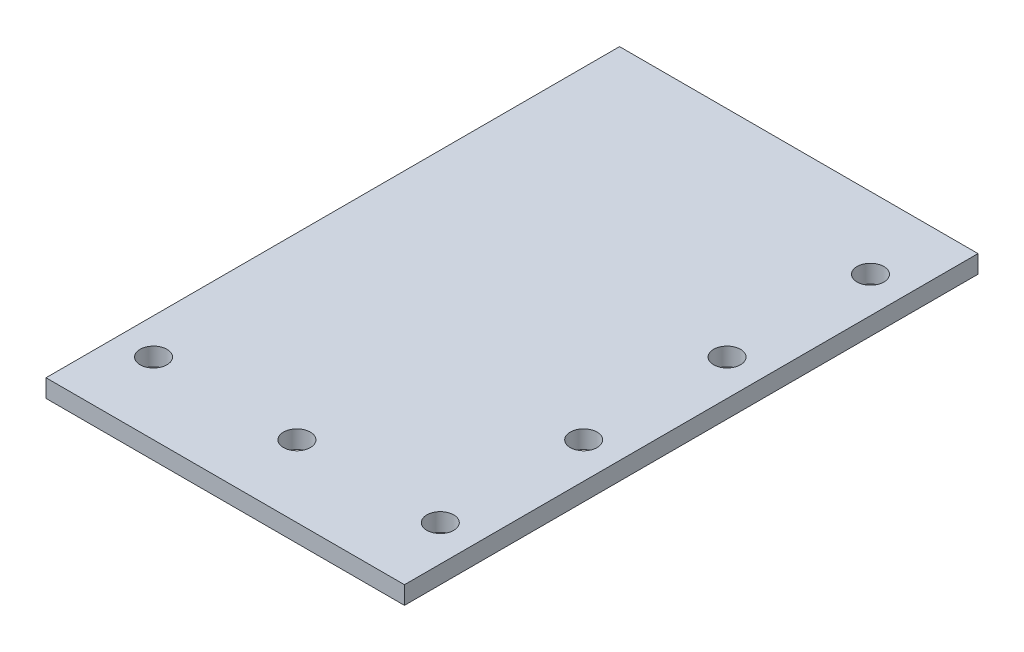
SolidWorks part; units mm, degrees
ref_plane "Front Plane" through (0, 0, 0) normal (0, 0, 1) x (1, 0, 0)
ref_plane "Top Plane" through (0, 0, 0) normal (0, 1, 0) x (1, 0, 0)
ref_plane "Right Plane" through (0, 0, 0) normal (1, 0, 0) x (0, 0, -1)
sketch "Sketch1" plane through (0, 0, 0) normal (0, 1, 0) x (1, 0, 0)
  line L1 (-31.75, 50.8) -> (31.75, 50.8)
  line L2 (-31.75, 50.8) -> (-31.75, -50.8)
  line L3 (-31.75, -50.8) -> (31.75, -50.8)
  line L4 (31.75, 50.8) -> (31.75, -50.8)
  line L5 (-31.75, 50.8) -> (31.75, -50.8) construction
  line L6 (-31.75, -50.8) -> (31.75, 50.8) construction
  point P0 (0, 0)
  dimension "D1" = 101.6
  dimension "D2" = 63.5
extrude "Boss-Extrude1" add sketch "Sketch1" along normal blind 3.175
sketch "Sketch2" plane through (0, 3.175, 0) normal (0, 1, 0) x (1, 0, 0)
  line L0 (-31.75, -50.8) -> (31.75, -50.8) construction
  line L1 (31.75, -50.8) -> (31.75, 50.8) construction
  circle A0 centre (25.4, -38.1) radius 2.3812
  circle A1 centre (25.4, -12.7) radius 2.3812
  circle A2 centre (25.4, 12.7) radius 2.3812
  circle A3 centre (25.4, 38.1) radius 2.3812
  circle A4 centre (0, -38.1) radius 2.3812
  circle A5 centre (-25.4, -38.1) radius 2.3812
  circle A6 centre (-50.8, -38.1) radius 2.3812
  dimension "D1" = 4.7625
  dimension "D2" = 12.7
  dimension "D3" = 6.35
  dimension "D4" = 4
  dimension "D5" = 4
extrude "Cut-Extrude1" cut sketch "Sketch2" against normal blind 3.175
